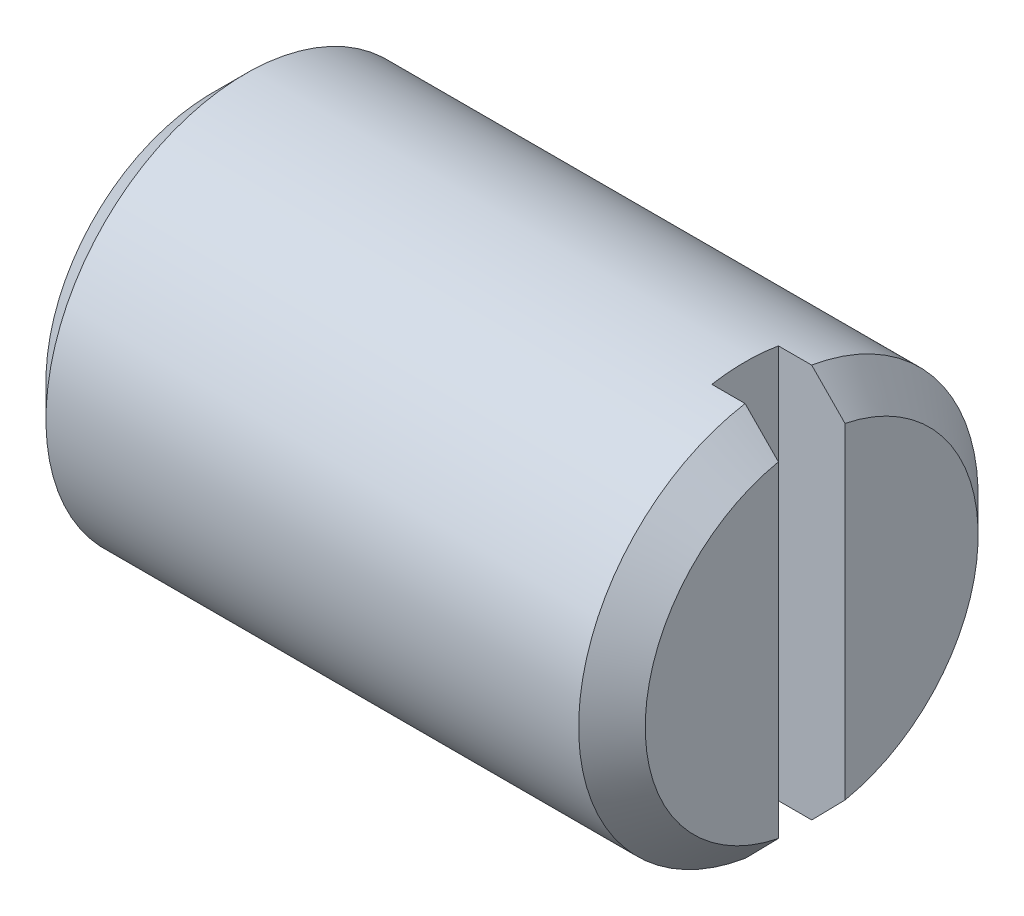
SolidWorks part; units mm, degrees
ref_plane "Alzado" through (0, 0, 0) normal (0, 0, 1) x (1, 0, 0)
ref_plane "Planta" through (0, 0, 0) normal (0, 1, 0) x (1, 0, 0)
ref_plane "Vista lateral" through (0, 0, 0) normal (1, 0, 0) x (0, 0, -1)
sketch "Croquis1" plane through (0, 0, 0) normal (1, 0, 0) x (0, 0, -1)
  circle A0 centre (0, 0) radius 3
  dimension "D1" = 6
extrude "Saliente-Extruir1" add sketch "Croquis1" along normal blind 9
sketch "Croquis2" plane through (9, 0, 0) normal (1, 0, 0) x (0, 0, -1)
  line L1 (-0.5, -3.5) -> (0.5, -3.5)
  line L2 (-0.5, -3.5) -> (-0.5, 3.5)
  line L3 (-0.5, 3.5) -> (0.5, 3.5)
  line L4 (0.5, -3.5) -> (0.5, 3.5)
  line L5 (-0.5, -3.5) -> (0.5, 3.5) construction
  line L6 (-0.5, 3.5) -> (0.5, -3.5) construction
  point P0 (0, 0)
  dimension "D1" = 1
  dimension "D2" = 7
extrude "Cortar-Extruir1" cut sketch "Croquis2" against normal blind 1
chamfer "Chaflán1" distance 0.5 angle 45 3 edges at (0, 0, -3) (9, 0, -3) (9, 0, 3)
